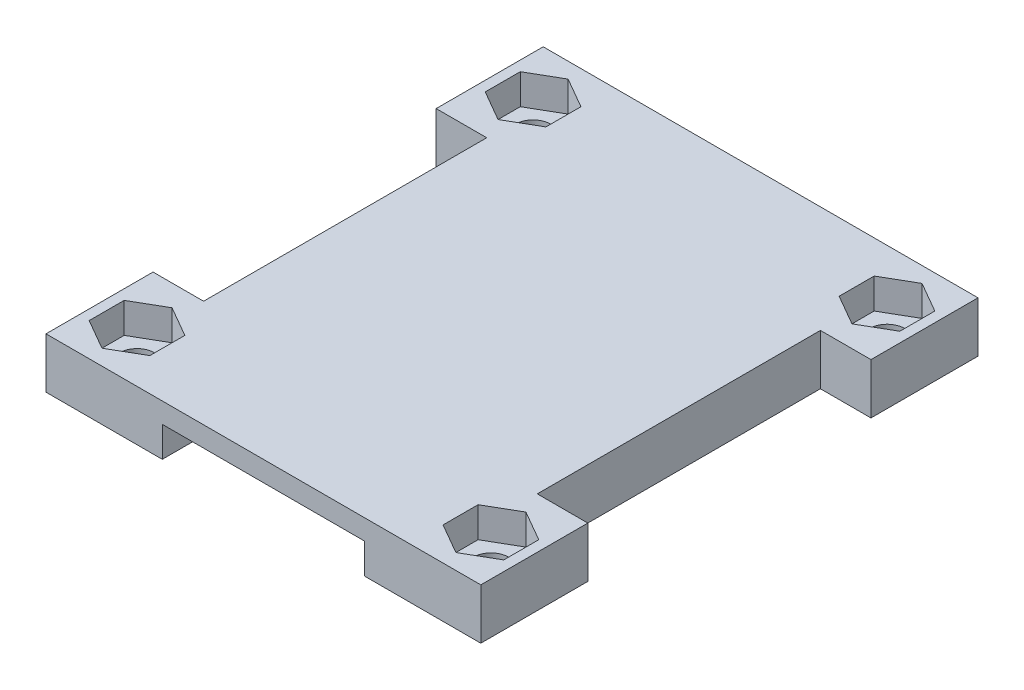
SolidWorks part; units mm, degrees
material "ABS"
ref_plane "Front Plane" through (0, 0, 0) normal (0, 0, 1) x (1, 0, 0)
ref_plane "Top Plane" through (0, 0, 0) normal (0, 1, 0) x (1, 0, 0)
ref_plane "Right Plane" through (0, 0, 0) normal (1, 0, 0) x (0, 0, -1)
sketch "Sketch1" plane through (0, 0, 0) normal (0, 1, 0) x (1, 0, 0)
  line L1 (0, 0) -> (-43, 0)
  line L2 (0, 0) -> (0, 49.17)
  line L3 (0, 49.17) -> (-43, 49.17)
  line L4 (-43, 0) -> (-43, 49.17)
  dimension "D1" = 43
  dimension "D2" = 49.17
extrude "Boss-Extrude1" add sketch "Sketch1" along normal blind 5
sketch "Sketch2" plane through (0, 5, 0) normal (0, 1, 0) x (1, 0, 0)
  line L0 (0, 49.17) -> (-43, 49.17) construction
  line L1 (0, 0) -> (-8, 0) construction
  line L2 (0, 0) -> (0, 49.17) construction
  line L3 (0, 49.17) -> (-8, 49.17) construction
  line L4 (-8, 0) -> (-8, 49.17) construction
  line L5 (-43, 0) -> (0, 0) construction
  line L6 (-43, 49.17) -> (-35, 49.17) construction
  line L7 (-43, 49.17) -> (-43, 0) construction
  line L8 (-43, 0) -> (-35, 0) construction
  line L9 (-35, 49.17) -> (-35, 0) construction
  line L10 (-4, 0) -> (-4, 5) construction
  line L11 (-21.5, 49.17) -> (-21.5, 0) construction
  line L12 (-43, 24.585) -> (0, 24.585) construction
  line L13 (-1, 42.4379) -> (-4, 40.7059)
  line L14 (-4, 8.4641) -> (-7, 6.7321)
  line L15 (-7, 6.7321) -> (-7, 3.2679)
  line L16 (-7, 3.2679) -> (-4, 1.5359)
  line L17 (-4, 1.5359) -> (-1, 3.2679)
  line L18 (-1, 3.2679) -> (-1, 6.7321)
  line L19 (-1, 6.7321) -> (-4, 8.4641)
  line L20 (-1, 45.9021) -> (-1, 42.4379)
  line L21 (-4, 47.6341) -> (-1, 45.9021)
  line L22 (-7, 45.9021) -> (-4, 47.6341)
  line L23 (-7, 42.4379) -> (-7, 45.9021)
  line L24 (-4, 40.7059) -> (-7, 42.4379)
  line L25 (-42, 6.7321) -> (-39, 8.4641)
  line L26 (-42, 3.2679) -> (-42, 6.7321)
  line L27 (-39, 1.5359) -> (-42, 3.2679)
  line L28 (-36, 3.2679) -> (-39, 1.5359)
  line L29 (-36, 6.7321) -> (-36, 3.2679)
  line L30 (-39, 8.4641) -> (-36, 6.7321)
  line L31 (-42, 45.9021) -> (-42, 42.4379)
  line L32 (-39, 47.6341) -> (-42, 45.9021)
  line L33 (-36, 45.9021) -> (-39, 47.6341)
  line L34 (-36, 42.4379) -> (-36, 45.9021)
  line L35 (-39, 40.7059) -> (-36, 42.4379)
  line L36 (-42, 42.4379) -> (-39, 40.7059)
  circle A0 centre (-4, 5) radius 3 construction
  dimension "D1" = 8
  dimension "D2" = 8
  dimension "D3" = 5
  dimension "D4" = 6
extrude "Cut-Extrude1" cut sketch "Sketch2" against normal blind 3
sketch "Sketch4" plane through (0, 2, 0) normal (0, 1, 0) x (1, 0, 0)
  line L0 (-39, 40.7059) -> (-39, 47.6341) construction
  line L1 (-21.5, 49.17) -> (-21.5, 0) construction
  line L2 (0, 49.17) -> (-43, 49.17) construction
  line L3 (-43, 0) -> (0, 0) construction
  line L4 (0, 24.585) -> (-43, 24.585) construction
  line L5 (0, 0) -> (0, 49.17) construction
  line L6 (-43, 49.17) -> (-43, 0) construction
  circle A0 centre (-39, 44.17) radius 1.75
  circle A1 centre (-39, 5) radius 1.75
  circle A2 centre (-4, 5) radius 1.75
  circle A3 centre (-4, 44.17) radius 1.75
  dimension "D1" = 3.5
extrude "Cut-Extrude2" cut sketch "Sketch4" against normal through all
sketch "Sketch5" plane through (0, 5, 0) normal (0, 1, 0) x (1, 0, 0)
  line L0 (0, 24.585) -> (-43, 24.585) construction
  line L1 (0, 0) -> (0, 49.17) construction
  line L2 (-43, 49.17) -> (-43, 0) construction
  line L3 (0, 24.585) -> (-5, 24.585) construction
  line L4 (-21.5, 49.17) -> (-21.5, 0) construction
  line L5 (0, 49.17) -> (-43, 49.17) construction
  line L6 (-43, 0) -> (0, 0) construction
  line L7 (-5, 10.585) -> (0, 10.585)
  line L9 (-5, 10.585) -> (-5, 38.585)
  line L10 (-5, 38.585) -> (0, 38.585)
  line L11 (0, 10.585) -> (0, 38.585)
  line L12 (-38, 10.585) -> (-38, 38.585)
  line L13 (-38, 38.585) -> (-43, 38.585)
  line L14 (-43, 10.585) -> (-43, 38.585)
  line L15 (-38, 10.585) -> (-43, 10.585)
  dimension "D1" = 5
  dimension "D2" = 14
extrude "Cut-Extrude3" cut sketch "Sketch5" against normal through all
sketch "Sketch7" plane through (0, 0, 0) normal (0, -1, 0) x (1, 0, 0)
  line L0 (-43, 0) -> (0, 0) construction
  line L1 (-11.5, 0) -> (-31.5, 0)
  line L2 (-31.5, 0) -> (-31.5, -49.17)
  line L3 (0, -49.17) -> (-43, -49.17) construction
  line L4 (-31.5, -49.17) -> (-11.5, -49.17)
  line L5 (-11.5, -49.17) -> (-11.5, 0)
  point P7 (-21.5, 0)
  dimension "D1" = 20
extrude "Cut-Extrude4" cut sketch "Sketch7" against normal blind 3
